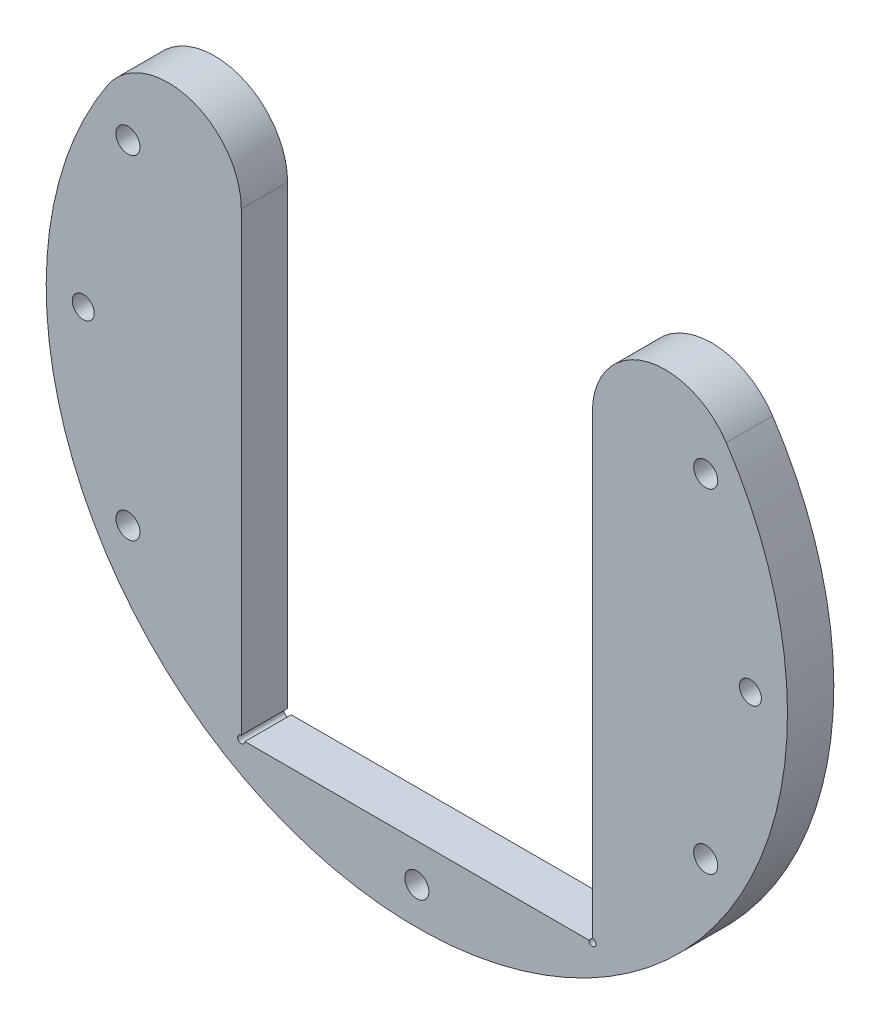
SolidWorks part; units mm, degrees
material "Acrylic (Medium-high impact)"
ref_plane "Front Plane" through (0, 0, 0) normal (0, 0, 1) x (1, 0, 0)
ref_plane "Top Plane" through (0, 0, 0) normal (0, 1, 0) x (1, 0, 0)
ref_plane "Right Plane" through (0, 0, 0) normal (1, 0, 0) x (0, 0, -1)
sketch "Sketch1" plane through (0, 0, 0) normal (0, 0, 1) x (1, 0, 0)
  line L0 (0, 0) -> (0, 76.2) construction
  line L2 (0, 0) -> (0, 40.5) construction
  line L3 (-24.0625, 40.5) -> (24.0625, 40.5) construction
  line L4 (24.0625, -40.5) -> (24.0625, 40.5)
  line L5 (0, 76.2) -> (0, -50.8) construction
  line L6 (-50.8, 0) -> (50.8, 0) construction
  line L7 (-24.0625, -40.5) -> (24.0625, -40.5)
  line L8 (-24.0625, -40.5) -> (-24.0625, 40.5)
  line L9 (-24.0625, 40.5) -> (-24.0625, 44.7396)
  line L10 (24.0625, 40.5) -> (24.0625, 44.7396)
  line L11 (0, 0) -> (-45.72, 0) construction
  arc A0 (-24.0625, 44.7396) -> (24.0625, 44.7396) centre (0, 0) ccw
  circle A1 centre (-45.72, 0) radius 1.5
  circle A2 centre (0, 45.72) radius 1.5 [skipped]
  circle A3 centre (45.72, 0) radius 1.5
  circle A4 centre (0, -45.72) radius 1.5 construction
  circle A5 centre (-39.5947, 22.86) radius 1.65
  circle A7 centre (0, 45.72) radius 1.65 construction
  circle A8 centre (39.5947, 22.86) radius 1.65
  circle A9 centre (39.5947, -22.86) radius 1.65
  circle A10 centre (0, -45.72) radius 1.65
  circle A11 centre (-39.5947, -22.86) radius 1.65
  point P13 (0, -40.5)
  point P20 (24.0625, -40.5)
  point P27 (0, 0)
  point P30 (-24.0625, -40.5)
  point P51 (0, 0)
  point P58 (0, 0)
  dimension "D1" = 50.8
  dimension "D3" = 45.72
  dimension "D5" = 3
  dimension "D6" = 40.5
  dimension "D7" = 45.72
  dimension "D8" = 3.3
  dimension "D2" = 48.125
  dimension "D4" = 4
  dimension "D9" = 6
extrude "Boss-Extrude1" add sketch "Sketch1" along normal blind 6.35 contours A0 L7 L8 L3 L4
fillet "Fillet2" radius 10 2 edges at (24.0625, 44.7396, 3.175) (-24.0625, 44.7396, 3.175)
sketch "Sketch2" plane through (0, 0, 6.35) normal (0, 0, 1) x (1, 0, 0)
  circle A0 centre (-24.0625, -40.5) radius 0.5
  circle A1 centre (24.0625, -40.5) radius 0.5
  dimension "D1" = 1
extrude "Cut-Extrude1" cut sketch "Sketch2" against normal through all
